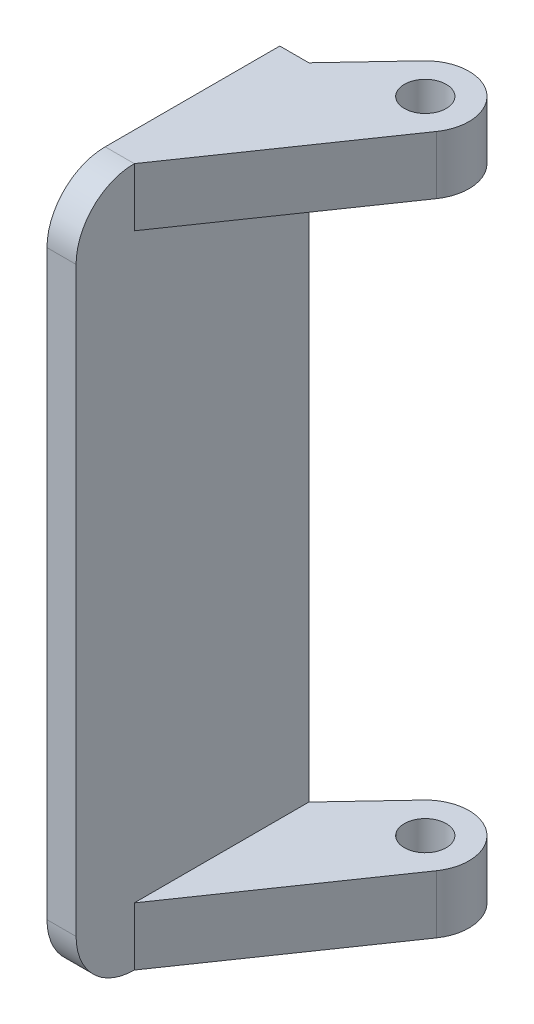
SolidWorks part; units mm, degrees
ref_plane "Front Plane" through (0, 0, 0) normal (0, 0, 1) x (1, 0, 0)
ref_plane "Top Plane" through (0, 0, 0) normal (0, 1, 0) x (1, 0, 0)
ref_plane "Right Plane" through (0, 0, 0) normal (1, 0, 0) x (0, 0, -1)
sketch "Sketch1" plane through (0, 0, 0) normal (0, 1, 0) x (1, 0, 0)
  line L0 (-12.7, -3.175) -> (-12.7, -28.575)
  line L1 (-12.7, -28.575) -> (-9.525, -28.575)
  line L2 (-9.525, -28.575) -> (-9.525, -22.225)
  line L3 (-9.525, -22.225) -> (3.9222, -2.7015)
  line L5 (-12.7, -3.175) -> (-9.525, -3.175)
  line L6 (-9.525, -3.175) -> (-3.4689, 3.2631)
  arc A0 (3.9222, -2.7015) -> (-3.4689, 3.2631) centre (0, 0) ccw
  point P1 (0, 0)
  point P9 (0, 0)
  dimension "D1" = 3.175
  dimension "D3" = 9.525
  dimension "D2" = 25.4
  dimension "D4" = 3.175
  dimension "D5" = 12.7
  dimension "D6" = 6.35
extrude "Boss-Extrude1" add sketch "Sketch1" along normal mid plane 76.2
sketch "Sketch2" plane through (0, 0, 0) normal (0, 1, 0) x (1, 0, 0)
  line L1 (-9.525, -22.225) -> (3.9222, -2.7015) construction
  line L2 (-3.4689, 3.2631) -> (-9.525, -3.175)
  line L3 (-9.525, -22.225) -> (3.9222, -2.7015)
  line L4 (-9.525, -22.225) -> (-9.525, -3.175)
  line L5 (-3.4689, 3.2631) -> (-9.525, -3.175) construction
  arc A0 (3.9222, -2.7015) -> (-3.4689, 3.2631) centre (0, 0) ccw construction
  arc A1 (3.9222, -2.7015) -> (-3.4689, 3.2631) centre (0, 0) ccw
  point P5 (-9.525, -0.9606)
extrude "Cut-Extrude1" cut sketch "Sketch2" along normal offset from surface 6.35 and the other way offset from surface (31.75 mm away) 6.35 up to face at (-7.2511, 38.1, 11.6769) other way up to face at (-7.2511, -38.1, 11.6769)
fillet "Fillet1" radius 6.35 2 edges at (-11.1125, -38.1, 28.575) (-11.1125, 38.1, 28.575)
sketch "Sketch3" plane through (0, 38.1, 0) normal (0, 1, 0) x (1, 0, 0)
  circle A0 centre (0, 0) radius 2.286
  dimension "D1" = 4.572
extrude "Cut-Extrude2" cut sketch "Sketch3" against normal through all
